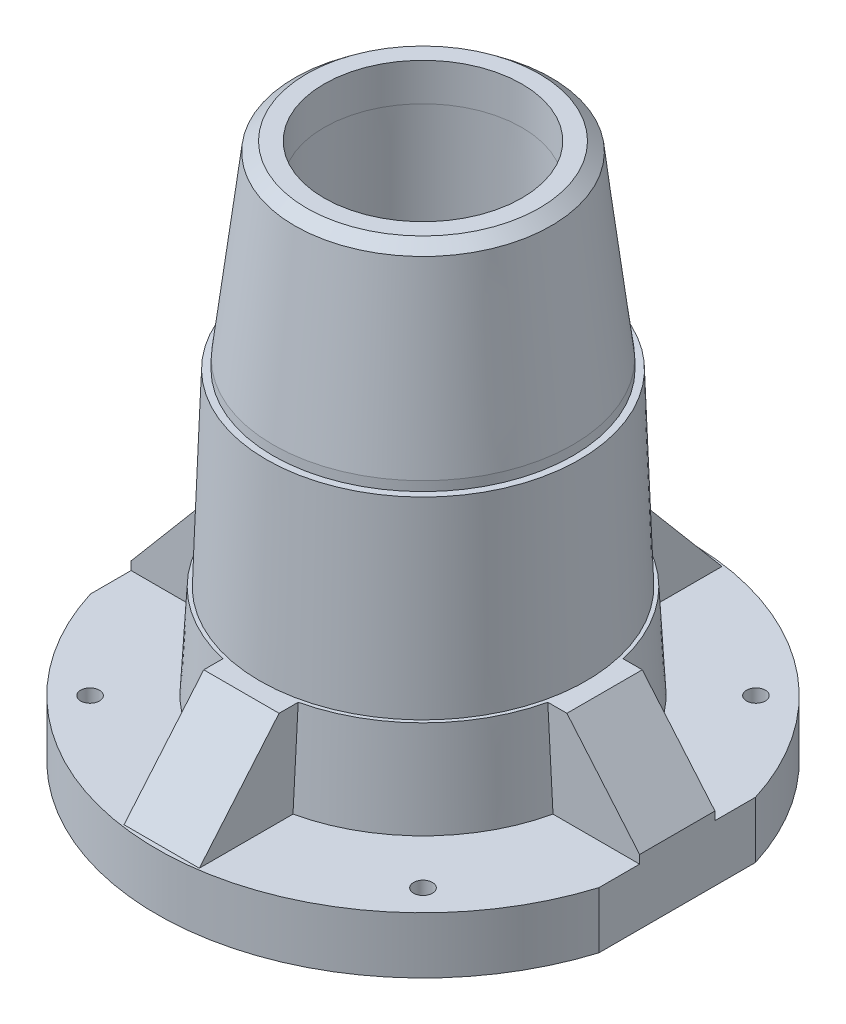
SolidWorks part; units mm, degrees
ref_plane "Front Plane" through (0, 0, 0) normal (0, 0, 1) x (1, 0, 0)
ref_plane "Top Plane" through (0, 0, 0) normal (0, 1, 0) x (1, 0, 0)
ref_plane "Right Plane" through (0, 0, 0) normal (1, 0, 0) x (0, 0, -1)
sketch "Sketch1" plane through (0, 0, 0) normal (1, 0, 0) x (0, 0, -1)
  line L0 (10.5, 57) -> (15.5, 57)
  line L1 (0, 0) -> (10.5, 0) construction
  line L2 (0, 0) -> (0, 57) construction
  line L3 (0, 57) -> (10.5, 57) construction
  line L4 (10.5, 0) -> (10.5, 57) construction
  line L5 (15.5, 57) -> (18.25, 6) construction
  line L6 (18.25, 6) -> (28.25, 6)
  line L7 (28.25, 6) -> (28.25, 0)
  line L8 (28.25, 0) -> (23.75, 0)
  line L9 (23.75, 0) -> (23.75, -3)
  line L10 (23.75, -3) -> (19.25, -3)
  line L11 (19.25, -3) -> (19.25, 0)
  line L12 (19.25, 0) -> (13.75, 0)
  line L13 (13.75, 0) -> (13.75, 6.7078)
  line L14 (13.75, 6.7078) -> (12.75, 6.7078)
  line L15 (12.75, 6.7078) -> (12.75, 8.0137)
  line L16 (12.75, 8.0137) -> (11.75, 8.0137)
  line L17 (11.75, 8.0137) -> (11.75, 36.0137)
  line L18 (11.75, 36.0137) -> (10.75, 36.0137)
  line L19 (10.75, 36.0137) -> (10.5, 53)
  line L21 (10.5, 53) -> (10.5, 57)
  line L22 (15.5, 57) -> (15.9216, 36.0137)
  line L23 (15.9216, 36.0137) -> (16.6316, 36.0137)
  line L24 (16.6316, 36.0137) -> (18.25, 6)
  point P5 (0, 0)
  point P24 (0, 0)
  point P25 (0, 0)
  point P26 (0, 0)
  dimension "D1" = 10.5
  dimension "D2" = 57
  dimension "D3" = 6
  dimension "D4" = 4.5
  dimension "D5" = 5
  dimension "D6" = 10
  dimension "D7" = 5.5
  dimension "D8" = 3
  dimension "D9" = 4
  dimension "D10" = 1
  dimension "D11" = 28
  dimension "D12" = 1.25
  dimension "D13" = 0.71
  dimension "D14" = 23.75
revolve "Revolve1" add sketch "Sketch1" angle 360 about L2
sketch "Sketch3" plane through (0, 0, 0) normal (0, 0, 1) x (1, 0, 0)
  line L0 (17.6029, 18) -> (27.75, 6)
  line L1 (18.25, 6) -> (16.6316, 36.0137) construction
  line L2 (28.25, 6) -> (-28.25, 6) construction
  dimension "D1" = 12
  dimension "D2" = 0.5
rib "Rib1" sketch "Sketch3" sketch "Sketch3" thickness 8 extrusion direction parallel to sketch draft on no parameters "D1"=8
chamfer "Chamfer1" distance 2 distance2 20 1 edges at (0, 57, -15.5)
chamfer "Chamfer2" distance 1 angle 45 1 edges at (0, 57, 13.5)
sketch "Sketch5" plane through (0, 0, 0) normal (0, -1, 0) x (1, 0, 0)
  line L0 (0, 0) -> (17.6777, -17.6777) construction
  line L1 (17.1102, -4) -> (17.8062, -4) construction
  circle A0 centre (17.6777, -17.6777) radius 1.25 construction
  circle A1 centre (0, 0) radius 23.75 construction
  circle A2 centre (17.6777, -17.6777) radius 1
  point P12 (18.2838, -18.2838)
  dimension "D2" = 2.5
  dimension "D4" = 2
  dimension "D1" = 45
  dimension "D3" = 0.25
sketch "Sketch7" plane through (0, 0, 0) normal (0, 1, 0) x (1, 0, 0)
  line L1 (27, -28.25) -> (-27, -28.25)
  line L2 (27, -28.25) -> (27, 28.25)
  line L3 (27, 28.25) -> (-27, 28.25)
  line L4 (-27, -28.25) -> (-27, 28.25)
  line L5 (27, -28.25) -> (-27, 28.25) construction
  line L6 (27, 28.25) -> (-27, -28.25) construction
  circle A0 centre (0, 0) radius 28.25 construction
  point P0 (0, 0)
  dimension "D1" = 54
pattern_circular "CirPattern23" count 4 over 360 about axis through (0, 0, 0) along (0, 1, 0) of "Rib1"
extrude "Cut-Extrude7" cut sketch "Sketch5" against normal up to next
pattern_circular "CirPattern24" count 4 over 360 about axis through (0, 0, 0) along (0, 1, 0) of "Cut-Extrude7"
sketch "Sketch4" plane through (0, 36.0137, 0) normal (0, 1, 0) x (1, 0, 0)
  circle A0 centre (0, 0) radius 16.6316 construction
  circle A1 centre (0, 0) radius 16.6316
extrude "Cut-Extrude8" cut sketch "Sketch4" against normal blind 20 draft 2 flip side to cut
extrude "Cut-Extrude9" cut sketch "Sketch7" along normal up to vertex (57 mm away) flip side to cut up to point (0, 57, 0)
